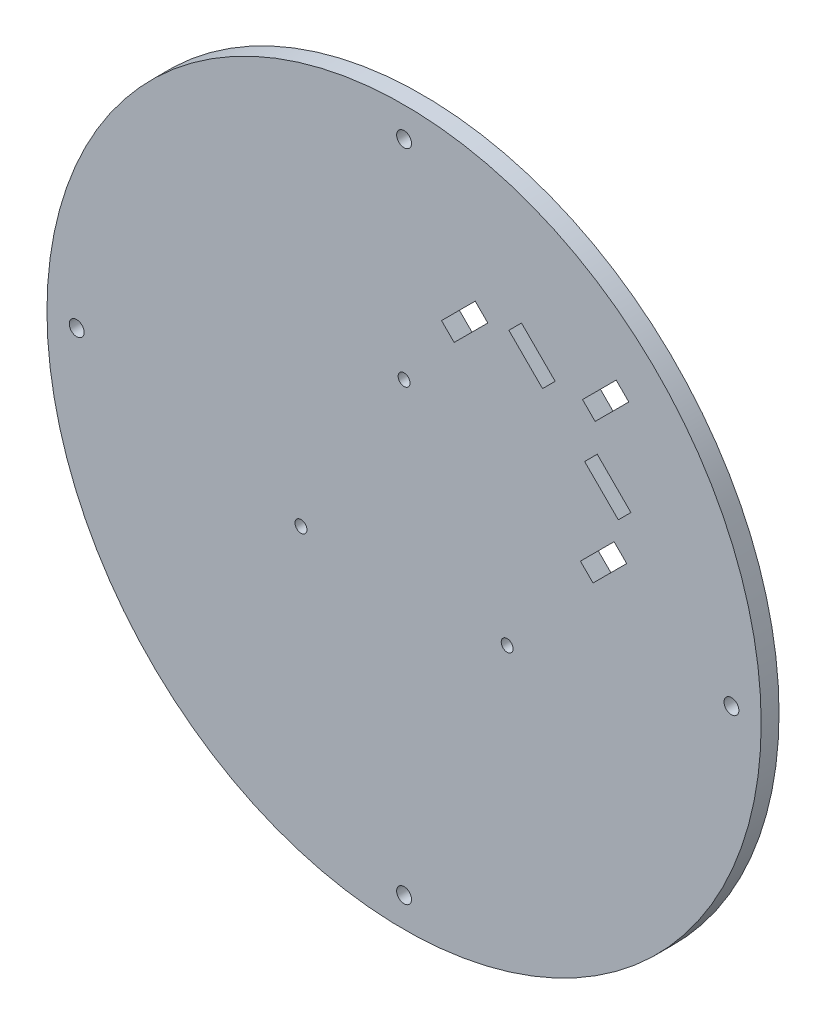
SolidWorks part; units mm, degrees
material "ABS PC"
ref_plane "前视基准面" through (0, 0, 0) normal (0, 0, 1) x (1, 0, 0)
ref_plane "上视基准面" through (0, 0, 0) normal (0, 1, 0) x (1, 0, 0)
ref_plane "右视基准面" through (0, 0, 0) normal (1, 0, 0) x (0, 0, -1)
sketch "草图1" plane through (0, 0, 0) normal (0, 0, 1) x (1, 0, 0)
  line L1 (0, -53.75) -> (0, -60) construction
  line L2 (0, 21) -> (0, 60) construction
  line L3 (0, 0) -> (0, 20) construction
  line L4 (0, 0) -> (-17.3205, -10) construction
  line L5 (35.9917, 17.607) -> (30.3349, 23.2638)
  line L6 (0, 0) -> (17.3205, -10) construction
  line L7 (-8.4853, 8.4853) -> (-42.4264, 42.4264) construction
  line L14 (53.75, 0) -> (60, 0) construction
  line L29 (25.0331, 25.0331) -> (25.0301, 25.0301)
  line L42 (25.0301, 25.0301) -> (25.0331, 25.0331)
  line L55 (38.1131, 19.7283) -> (35.9917, 17.607)
  line L56 (23.2638, 30.3349) -> (25.3851, 32.4562)
  line L57 (25.3851, 32.4562) -> (19.7283, 38.1131)
  line L58 (19.7283, 38.1131) -> (17.607, 35.9917)
  line L59 (17.607, 35.9917) -> (23.2638, 30.3349)
  line L60 (11.9501, 37.4059) -> (14.0714, 35.2846)
  line L61 (32.4562, 25.3851) -> (38.1131, 19.7283)
  line L63 (14.0714, 35.2846) -> (8.4146, 29.6278)
  line L64 (8.4146, 29.6278) -> (6.2933, 31.7491)
  line L65 (6.2933, 31.7491) -> (11.9501, 37.4059)
  line L67 (30.3349, 23.2638) -> (32.4562, 25.3851)
  line L68 (31.7491, 6.2933) -> (37.4059, 11.9501)
  line L69 (29.6278, 8.4146) -> (31.7491, 6.2933)
  line L70 (35.2846, 14.0714) -> (29.6278, 8.4146)
  line L71 (37.4059, 11.9501) -> (35.2846, 14.0714)
  line L72 (25.0301, 25.0301) -> (28.9207, 28.9207)
  line L73 (25.3851, 32.4562) -> (32.4562, 25.3851)
  line L74 (29.9813, 32.1026) -> (32.1026, 29.9813)
  line L76 (29.9813, 32.1026) -> (35.6382, 37.7595)
  line L77 (35.6382, 37.7595) -> (37.7595, 35.6382)
  line L78 (37.7595, 35.6382) -> (32.1026, 29.9813)
  line L81 (-53.75, 0) -> (-60, 0) construction
  circle A0 centre (0, 0) radius 60
  circle A1 centre (55, 0) radius 1.25
  circle A2 centre (0, 55) radius 1.25
  circle A3 centre (0, -55) radius 1.25
  circle A4 centre (-55, 0) radius 1.25
  circle A6 centre (0, 20) radius 1
  circle A7 centre (17.3205, -10) radius 1
  circle A8 centre (-17.3205, -10) radius 1
  dimension "D9" = 55
  dimension "D11" = 3
  dimension "D17" = 8
  dimension "D4" = 3
  dimension "D20" = 120
  dimension "D3" = 120
  dimension "D5" = 120
  dimension "D6" = 2
  dimension "D8" = 2
  dimension "D7" = 20
  dimension "D10" = 8
  dimension "D12" = 8
  dimension "D13" = 3
  dimension "D14" = 11
  dimension "D15" = 3
  dimension "D16" = 8
  dimension "D18" = 3.5
  dimension "D19" = 3.5
  dimension "D21" = 20
  dimension "D22" = 20
extrude "凸台-拉伸1" add sketch "草图1" along normal blind 3
cosmetic thread "装饰螺纹线1" parameters "D2"=3
cosmetic thread "装饰螺纹线2" parameters "D2"=3
cosmetic thread "装饰螺纹线3" parameters "D2"=3
cosmetic thread "装饰螺纹线4" parameters "D2"=3
